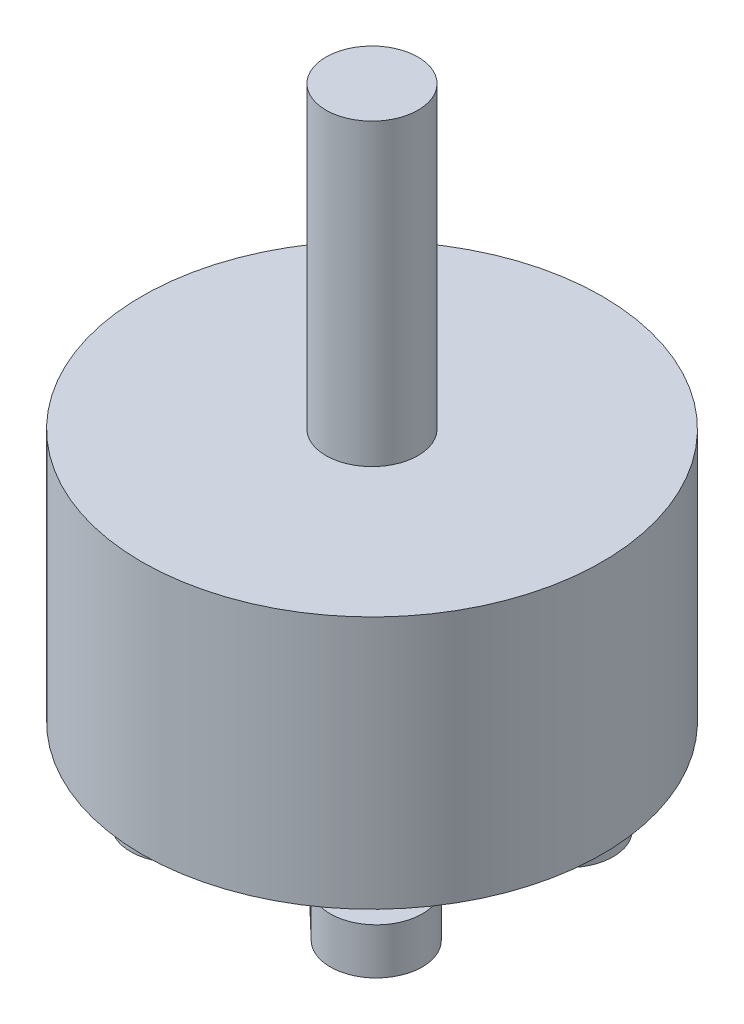
SolidWorks part; units mm, degrees
ref_plane "Front Plane" through (0, 0, 0) normal (0, 0, 1) x (1, 0, 0)
ref_plane "Top Plane" through (0, 0, 0) normal (0, 1, 0) x (1, 0, 0)
ref_plane "Right Plane" through (0, 0, 0) normal (1, 0, 0) x (0, 0, -1)
sketch "Sketch2" plane through (0, 0, 0) normal (0, 1, 0) x (1, 0, 0)
  circle A0 centre (0, 0) radius 10
  dimension "D1" = 20
extrude "Boss-Extrude2" add sketch "Sketch2" along normal blind 30
sketch "Sketch8" plane through (0, 30, 0) normal (0, 1, 0) x (1, 0, 0)
  circle A0 centre (0, 0) radius 4
  circle A1 centre (0, 0) radius 10
extrude "Cut-Extrude5" cut sketch "Sketch8" against normal blind 13
sketch "Sketch9" plane through (0, 30, 0) normal (0, 1, 0) x (1, 0, 0)
  circle A0 centre (0, 0) radius 2
  circle A1 centre (0, 0) radius 4
extrude "Cut-Extrude6" cut sketch "Sketch9" against normal blind 13
sketch "Sketch10" plane through (0, 0, 0) normal (0, -1, 0) x (1, 0, 0)
  circle A0 centre (0, 0) radius 1
  circle A1 centre (0, 0) radius 10
extrude "Cut-Extrude7" cut sketch "Sketch10" against normal blind 1
sketch "Sketch11" plane through (0, 0, 0) normal (0, -1, 0) x (-1, 0, 0)
  circle A0 centre (0, 0) radius 2
  circle A1 centre (0, 0) radius 10
extrude "Cut-Extrude8" cut sketch "Sketch11" against normal blind 2
sketch "Sketch12" plane through (0, 0, 0) normal (0, -1, 0) x (-1, 0, 0)
  line L0 (4.3346, -4.1487) -> (-4.3346, 4.1487) construction
  line L1 (4.3346, -4.1487) -> (-4.3346, -4.1487)
  line L2 (4.3346, -4.1487) -> (4.3346, 4.1487)
  line L3 (4.3346, 4.1487) -> (-4.3346, 4.1487)
  line L4 (-4.3346, -4.1487) -> (-4.3346, 4.1487)
  line L5 (4.3346, -4.1487) -> (-4.3346, 4.1487) construction
  line L6 (4.3346, 4.1487) -> (-4.3346, -4.1487) construction
  line L7 (2.9517, -5.5935) -> (-5.7175, 2.7038)
  line L8 (5.7175, -2.7038) -> (-2.9517, 5.5935)
  line L9 (-4.3346, -4.1487) -> (4.3346, 4.1487) construction
  line L10 (-5.7175, -2.7038) -> (2.9517, 5.5935)
  line L11 (-2.9517, -5.5935) -> (5.7175, 2.7038)
  circle A0 centre (4.3346, -4.1487) radius 1
  circle A1 centre (4.3346, 4.1487) radius 1
  circle A2 centre (-4.3346, 4.1487) radius 1
  circle A3 centre (-4.3346, -4.1487) radius 1
  arc A4 (2.9517, -5.5935) -> (5.7175, -2.7038) centre (4.3346, -4.1487) ccw
  arc A5 (-2.9517, 5.5935) -> (-5.7175, 2.7038) centre (-4.3346, 4.1487) ccw
  arc A6 (-5.7175, -2.7038) -> (-2.9517, -5.5935) centre (-4.3346, -4.1487) ccw
  arc A7 (5.7175, 2.7038) -> (2.9517, 5.5935) centre (4.3346, 4.1487) ccw
  circle A8 centre (0, 0) radius 10
  point P0 (0, 0)
  point P10 (0, 0)
  point P15 (0, 0)
  dimension "D3" = 2
  dimension "D4" = 2
  dimension "D1" = 12
  dimension "D2" = 12
extrude "Cut-Extrude9" cut sketch "Sketch12" against normal blind 4 contours A8 A7 L11 L2 L8 A4 L7 L1 A6 L10 L4 A5 L3
sketch "Sketch13" plane through (0, 4, 0) normal (0, -1, 0) x (1, 0, 0)
  circle A0 centre (0, 0) radius 4
  circle A1 centre (0, 0) radius 10
extrude "Cut-Extrude10" cut sketch "Sketch13" against normal blind 2
sketch "Sketch14" plane through (0, 2, 0) normal (0, -1, 0) x (1, 0, 0)
  circle A0 centre (-4.2875, 4.1996) radius 1
  arc A1 (-2.9517, 5.5935) -> (-5.7175, 2.7038) centre (-4.3346, 4.1487) ccw construction
  circle A2 centre (4.3905, 4.0925) radius 1
  arc A3 (5.7175, 2.7038) -> (2.9517, 5.5935) centre (4.3346, 4.1487) ccw construction
  circle A4 centre (4.3548, -4.1279) radius 1
  arc A5 (2.9517, -5.5935) -> (5.7175, -2.7038) centre (4.3346, -4.1487) ccw construction
  circle A6 centre (-4.3228, -4.1611) radius 1
  arc A7 (-5.7175, -2.7038) -> (-2.9517, -5.5935) centre (-4.3346, -4.1487) ccw construction
  point P2 (-5.7794, 5.5316)
  point P8 (5.7794, 5.5316)
  point P14 (5.7794, -5.5316)
  point P20 (-5.7794, -5.5316)
  dimension "D1" = 2
  dimension "D2" = 2
  dimension "D3" = 2
  dimension "D4" = 2
extrude "Cut-Extrude11" cut sketch "Sketch14" against normal blind 2
